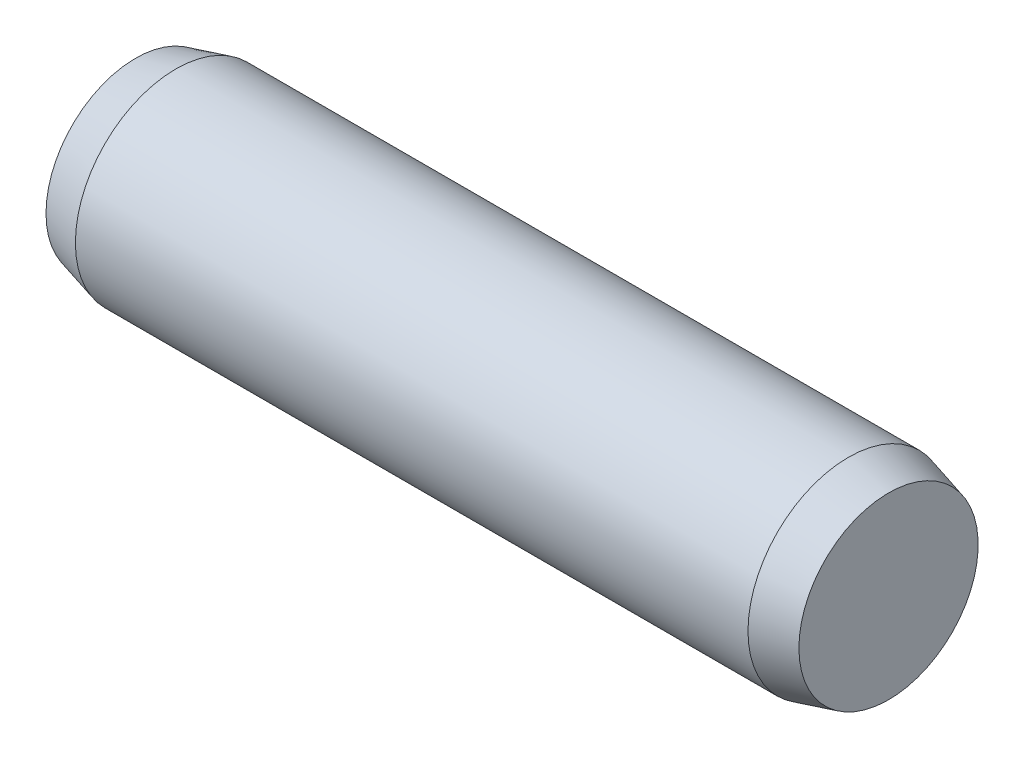
SolidWorks part; units mm, degrees
ref_plane "Front" through (0, 0, 0) normal (0, 0, 1) x (1, 0, 0)
ref_plane "Top" through (0, 0, 0) normal (0, 1, 0) x (1, 0, 0)
ref_plane "Right" through (0, 0, 0) normal (1, 0, 0) x (0, 0, -1)
sketch "Sketch1" plane through (0, 0, 0) normal (0, 0, 1) x (1, 0, 0)
  line L0 (0, 0) -> (3, 0)
  line L1 (3, 0) -> (3, 0.3571)
  line L2 (3, 0.3571) -> (2.84, 0.4)
  line L3 (2.84, 0.4) -> (0.16, 0.4)
  line L4 (0.16, 0.4) -> (0, 0.3571)
  line L5 (0, 0.3571) -> (0, 0)
  line L6 (-1.6557, 0) -> (2.6973, 0) construction
  dimension "l" = 3
  dimension "D2" = 15
  dimension "D3" = 15
  dimension "d" = 0.8
  dimension "c" = 0.16
  dimension "D6" = 0.16
revolve "Base-Revolve" add sketch "Sketch1" angle 360 about L6
equation "\"D6@Sketch1\" = \"c@Sketch1\""
